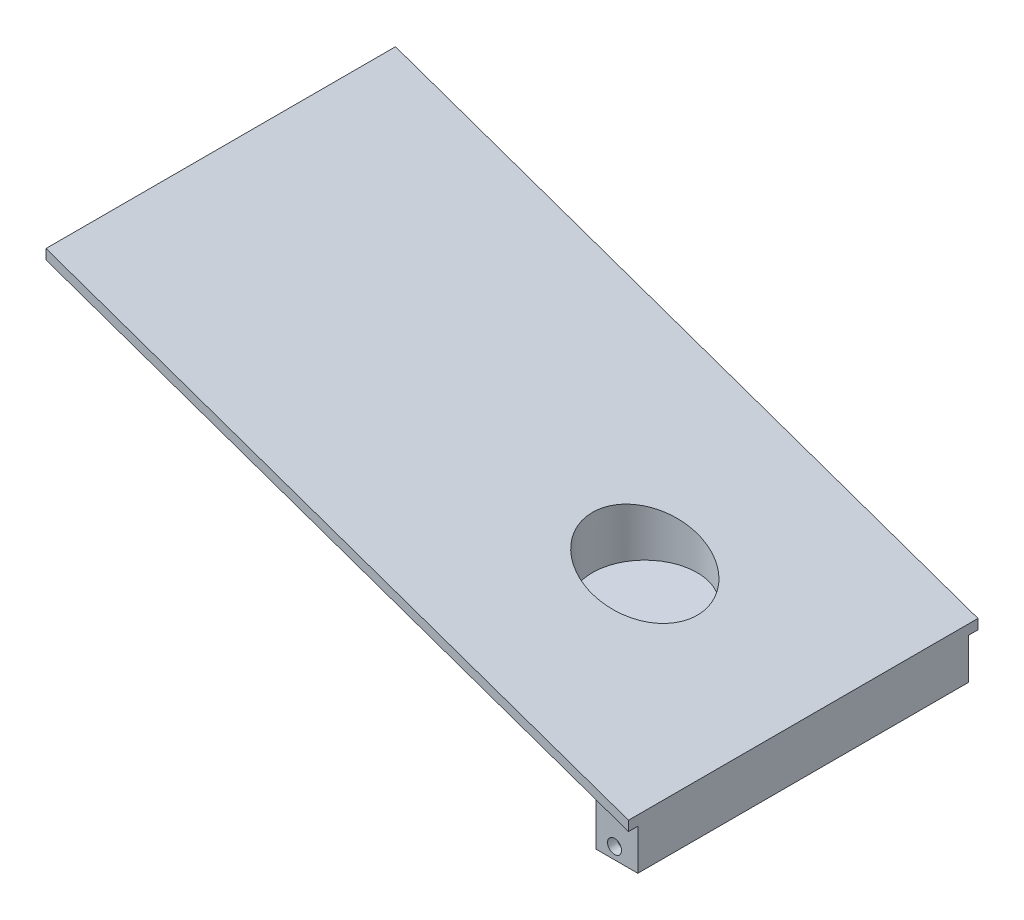
SolidWorks part; units mm, degrees
ref_plane "Front Plane" through (0, 0, 0) normal (0, 0, 1) x (1, 0, 0)
ref_plane "Top Plane" through (0, 0, 0) normal (0, 1, 0) x (1, 0, 0)
ref_plane "Right Plane" through (0, 0, 0) normal (1, 0, 0) x (0, 0, -1)
sketch "Sketch1" plane through (0, 0, 0) normal (0, 0, 1) x (1, 0, 0)
  line L0 (0, 0) -> (0, 21.74)
  line L1 (0, 21.74) -> (-249.9998, 109.2397)
  line L2 (-249.9998, 109.2397) -> (-249.9998, 104.9997)
  line L3 (-249.9998, 104.9997) -> (-18, 23.8)
  line L4 (-18, 23.8) -> (-18, 0)
  line L5 (-18, 0) -> (0, 0)
  dimension "D1" = 21.74
  dimension "D2" = 109.29
  dimension "D3" = 18
  dimension "D4" = 264.87
  dimension "D5" = 23.8
extrude "Boss-Extrude1" add sketch "Sketch1" along normal blind 150
sketch "Sketch2" plane through (0, 0, 150) normal (0, 0, 1) x (1, 0, 0)
  line L0 (-18, 23.8) -> (0, 17.5)
  line L1 (0, 0) -> (0, 21.74) construction
  line L2 (-18, 23.8) -> (-18, 28.04) construction
  line L3 (0, 21.74) -> (-249.9998, 109.2397) construction
  line L4 (-18, 23.8) -> (-18, 0)
  line L5 (-18, 0) -> (0, 0)
  line L6 (0, 0) -> (0, 17.5)
  dimension "D1" = 109.29
extrude "Cut-Extrude1" cut sketch "Sketch2" against normal blind 4
sketch "Sketch3" plane through (0, 0, 0) normal (0, 0, -1) x (-1, 0, 0)
  line L0 (18, 0) -> (18, 23.8)
  line L1 (18, 23.8) -> (0, 17.5)
  line L2 (0, 0) -> (0, 21.74) construction
  line L3 (0, 17.5) -> (0, 0)
  line L4 (0, 0) -> (18, 0)
  line L5 (18, 23.8) -> (18, 28.04) construction
  line L6 (0, 21.74) -> (249.9998, 109.2397) construction
  dimension "D1" = 109.29
extrude "Cut-Extrude2" cut sketch "Sketch3" against normal blind 4
sketch "Sketch4" plane through (0, 0, 4) normal (0, 0, -1) x (-1, 0, 0)
  line L0 (0, 17.5) -> (0, 0) construction
  line L2 (0, 0) -> (18, 0) construction
  circle A0 centre (10, 5) radius 3
  dimension "D1" = 6
  dimension "D3" = 5
  dimension "D2" = 10
extrude "Cut-Extrude3" cut sketch "Sketch4" against normal blind 162
sketch "Sketch6" plane through (-18, 0, 0) normal (-1, 0, 0) x (0, 0, 1)
  line L0 (146, 0) -> (4, 0) construction
  line L1 (8, 0) -> (142, 0)
  line L2 (8, 0) -> (8, 17.5)
  line L3 (8, 17.5) -> (142, 17.5)
  line L4 (142, 0) -> (142, 17.5)
  line L5 (4, 0) -> (4, 23.8) construction
  line L6 (146, 23.8) -> (146, 0) construction
  dimension "D1" = 4
  dimension "D2" = 4
  dimension "D3" = 17.5
extrude "Cut-Extrude4" cut sketch "Sketch6" against normal blind 14
sketch "Sketch9" plane through (0, 0, 0) normal (0, 1, 0) x (1, 0, 0)
  line L0 (-249.9998, -150) -> (0, -150) construction
  line L1 (-18, -142) -> (-18, -8) construction
  circle A0 centre (-68, -75) radius 22.5
  dimension "D1" = 45
  dimension "D2" = 75
  dimension "D3" = 50
extrude "Cut-Extrude5" cut sketch "Sketch9" along normal blind 83
sketch "Sketch10" plane through (0, 0, 0) normal (0, 1, 0) x (1, 0, 0)
  line L0 (-18, -142) -> (-18, -8) construction
  line L1 (-249.9998, -150) -> (0, -150) construction
  circle A0 centre (-68, -75) radius 26.5
  dimension "D1" = 53
  dimension "D2" = 50
  dimension "D3" = 75
extrude "Boss-Extrude2" add sketch "Sketch10" along normal blind 55
sketch "Sketch12" plane through (0, 0, 0) normal (0, -1, 0) x (1, 0, 0)
  circle A0 centre (-68, 75) radius 26.5
extrude "Cut-Extrude6" cut sketch "Sketch12" against normal blind 27
sketch "Sketch13" plane through (0, 55, 0) normal (0, 1, 0) x (1, 0, 0)
  circle A0 centre (-68, -75) radius 22.5
  dimension "D1" = 45
extrude "Cut-Extrude7" cut sketch "Sketch13" against normal blind 24
sketch "Sketch14" plane through (5.4566, 15.5902, 0) normal (-0.3303, -0.9439, 0) x (0.9439, -0.3303, 0)
  line L0 (-270.6511, 150) -> (-5.7811, 150) construction
  line L1 (-266.6511, 4) -> (-201.6511, 4)
  line L2 (-266.6511, 4) -> (-266.6511, 146)
  line L3 (-266.6511, 146) -> (-201.6511, 146)
  line L4 (-201.6511, 4) -> (-201.6511, 146)
  line L5 (-270.6511, 0) -> (-5.7811, 0) construction
  line L6 (-270.6511, 150) -> (-270.6511, 0) construction
  dimension "D1" = 4
  dimension "D2" = 4
  dimension "D3" = 4
  dimension "D4" = 65
extrude "Cut-Extrude8" cut sketch "Sketch14" against normal blind 2
sketch "Sketch15" plane through (6.7786, 19.3675, 0) normal (0.3303, 0.9439, 0) x (0.9439, -0.3303, 0)
  line L1 (-112.8112, -47.353) -> (-39.7621, -47.353)
  line L2 (-112.8112, -47.353) -> (-112.8112, -103.997)
  line L3 (-112.8112, -103.997) -> (-39.7621, -103.997)
  line L4 (-39.7621, -47.353) -> (-39.7621, -103.997)
extrude "Cut-Extrude9" cut sketch "Sketch15" along normal blind 22
